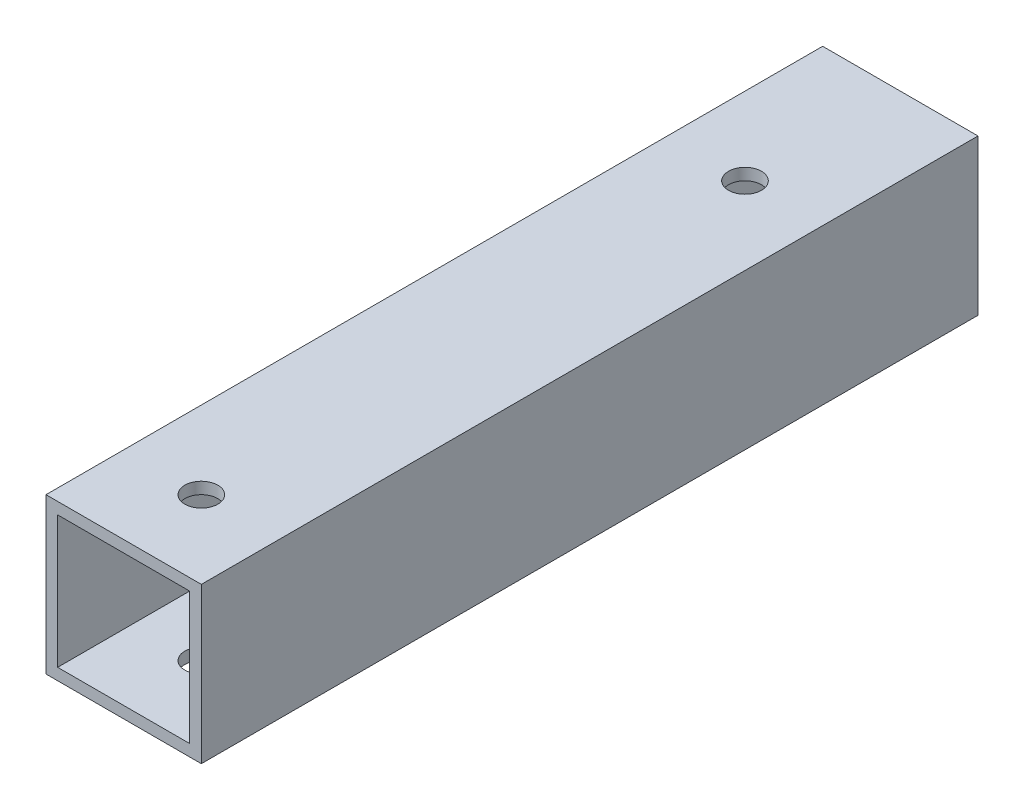
SolidWorks part; units mm, degrees
ref_plane "Front Plane" through (0, 0, 0) normal (0, 0, 1) x (1, 0, 0)
ref_plane "Top Plane" through (0, 0, 0) normal (0, 1, 0) x (1, 0, 0)
ref_plane "Right Plane" through (0, 0, 0) normal (1, 0, 0) x (0, 0, -1)
sketch "Sketch1" plane through (0, 0, 0) normal (0, 0, 1) x (1, 0, 0)
  line L0 (-8.5, -8.5) -> (8.5, -8.5)
  line L1 (-10, -10) -> (10, -10)
  line L2 (-10, -10) -> (-10, 10)
  line L3 (-10, 10) -> (10, 10)
  line L4 (10, -10) -> (10, 10)
  line L5 (-10, -10) -> (10, 10) construction
  line L6 (-10, 10) -> (10, -10) construction
  line L7 (8.5, -8.5) -> (8.5, 8.5)
  line L8 (-8.5, 8.5) -> (8.5, 8.5)
  line L9 (-8.5, -8.5) -> (-8.5, 8.5)
  point P0 (0, 0)
  dimension "D1" = 20
  dimension "D3" = 20
  dimension "D2" = 1.5
extrude "Boss-Extrude1" add sketch "Sketch1" against normal blind 100
sketch "Sketch2" plane through (0, 10, 0) normal (0, 1, 0) x (1, 0, 0)
  line L0 (10, 0) -> (-10, 0) construction
  circle A0 centre (0, 10) radius 2.125
  circle A6 centre (0, 80) radius 2.125
  circle A7 centre (0, 150) radius 2.125
  dimension "D1" = 4.25
  dimension "D2" = 10
extrude "Cut-Extrude1" cut sketch "Sketch2" against normal through all
